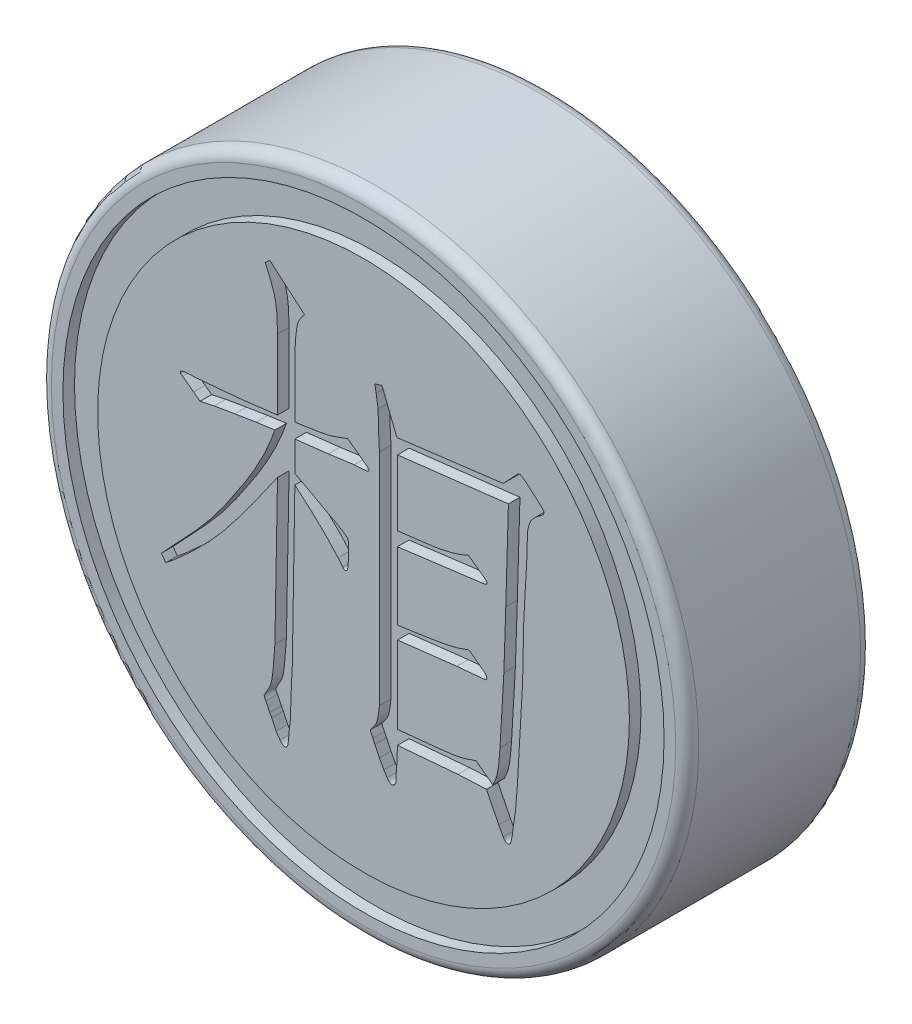
SolidWorks part; units mm, degrees
ref_plane "前视基准面" through (0, 0, 0) normal (0, 0, 1) x (1, 0, 0)
ref_plane "上视基准面" through (0, 0, 0) normal (0, 1, 0) x (1, 0, 0)
ref_plane "右视基准面" through (0, 0, 0) normal (1, 0, 0) x (0, 0, -1)
sketch "草图1" plane through (0, 0, 0) normal (0, 0, 1) x (1, 0, 0)
  circle A0 centre (0, 0) radius 14
extrude "凸台-拉伸1" add sketch "草图1" along normal blind 8
sketch "草图2" plane through (0, 0, 8) normal (0, 0, 1) x (1, 0, 0)
  circle A0 centre (0, 0) radius 13
  circle A1 centre (0, 0) radius 11.5
extrude "切除-拉伸1" cut sketch "草图2" against normal blind 0.5
sketch "草图3" plane through (0, 0, 0) normal (0, 0, -1) x (-1, 0, 0)
  circle A0 centre (0, 0) radius 5.1
extrude "切除-拉伸2" cut sketch "草图3" against normal blind 5
chamfer "倒角1" distance 0.5 angle 45 1 edges at (-5.1, 0, 0)
fillet "圆角1" radius 0.5 2 edges at (14, 0, 8) (14, 0, 0)
sketch "草图4" plane through (0, 0, 8) normal (0, 0, 1) x (1, 0, 0)
  text T0 "相" font "汉仪长仿宋体" height 13
extrude "切除-拉伸3" cut sketch "草图4" against normal blind 0.5
